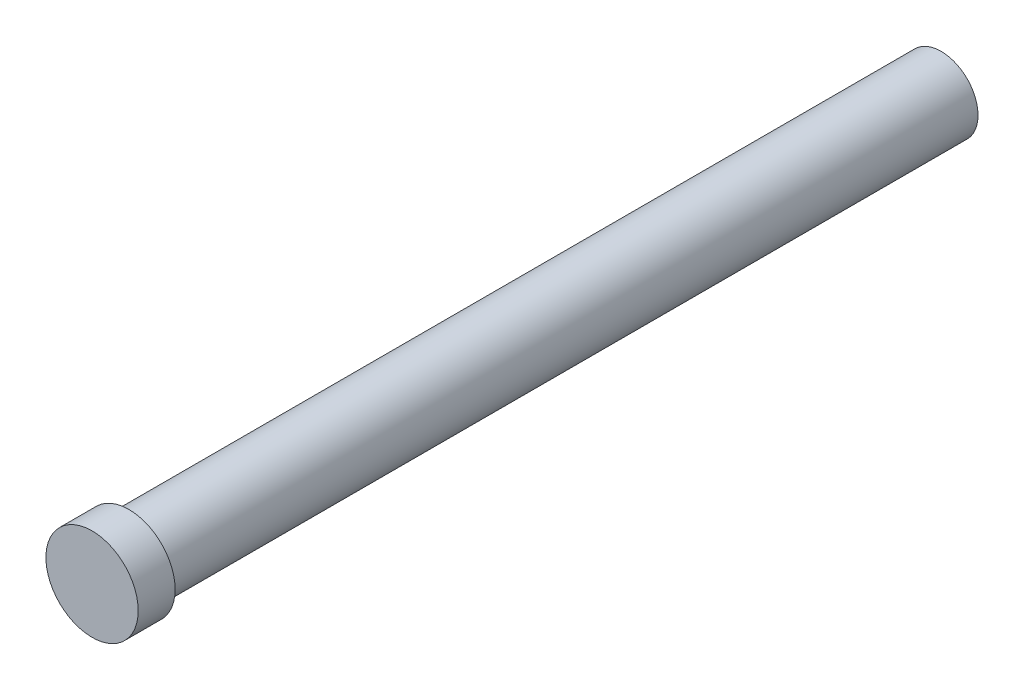
SolidWorks part; units mm, degrees
ref_plane "Front Plane" through (0, 0, 0) normal (0, 0, 1) x (1, 0, 0)
ref_plane "Top Plane" through (0, 0, 0) normal (0, 1, 0) x (1, 0, 0)
ref_plane "Right Plane" through (0, 0, 0) normal (1, 0, 0) x (0, 0, -1)
sketch "Sketch1" plane through (0, 0, 0) normal (0, 0, 1) x (1, 0, 0)
  circle A0 centre (0, 0) radius 1
  dimension "D1" = 2
extrude "Boss-Extrude1" add sketch "Sketch1" along normal blind 22
sketch "Sketch2" plane through (0, 0, 22) normal (0, 0, 1) x (1, 0, 0)
  circle A0 centre (0, 0) radius 1.25
  dimension "D1" = 2.5
extrude "Boss-Extrude2" add sketch "Sketch2" along normal blind 1
